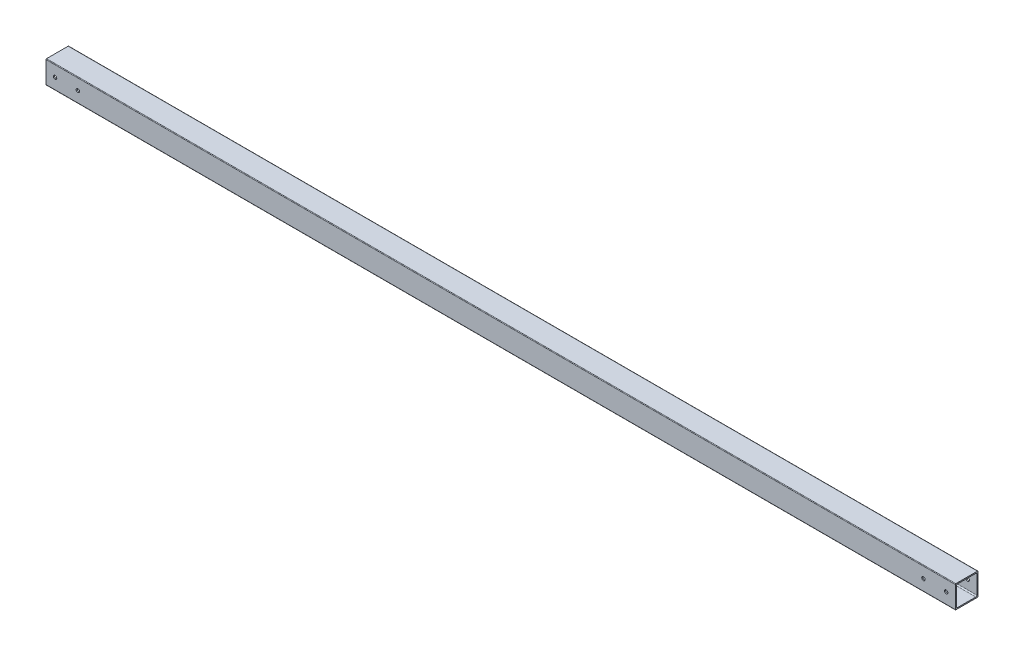
SolidWorks part; units mm, degrees
material "Thornel Mat VMA"
ref_plane "Front Plane" through (0, 0, 0) normal (0, 0, 1) x (1, 0, 0)
ref_plane "Top Plane" through (0, 0, 0) normal (0, 1, 0) x (1, 0, 0)
ref_plane "Right Plane" through (0, 0, 0) normal (1, 0, 0) x (0, 0, -1)
sketch "Sketch1" plane through (0, 0, 0) normal (1, 0, 0) x (0, 0, -1)
  line L1 (-9.5, -10) -> (9.5, -10)
  line L2 (-10, -9.5) -> (-10, 9.5)
  line L3 (-9.5, 10) -> (9.5, 10)
  line L4 (10, -9.5) -> (10, 9.5)
  line L5 (-10, -10) -> (10, 10) construction
  line L6 (-10, 10) -> (10, -10) construction
  line L7 (-8, -9) -> (8, -9)
  line L8 (-9, -8) -> (-9, 8)
  line L9 (-8, 9) -> (8, 9)
  line L10 (9, -8) -> (9, 8)
  line L11 (-9, -9) -> (9, 9) construction
  line L12 (-9, 9) -> (9, -9) construction
  arc A0 (-9.5, -10) -> (-10, -9.5) centre (-9.5, -9.5) cw
  arc A1 (9.5, -10) -> (10, -9.5) centre (9.5, -9.5) ccw
  arc A2 (9.5, 10) -> (10, 9.5) centre (9.5, 9.5) cw
  arc A3 (-10, 9.5) -> (-9.5, 10) centre (-9.5, 9.5) cw
  arc A4 (-8, -9) -> (-9, -8) centre (-8, -8) cw
  arc A5 (8, -9) -> (9, -8) centre (8, -8) ccw
  arc A6 (8, 9) -> (9, 8) centre (8, 8) cw
  arc A7 (-9, 8) -> (-8, 9) centre (-8, 8) cw
  point P0 (0, 0)
  point P6 (0, 0)
  dimension "D5" = 0.5
  dimension "D6" = 1
  dimension "D1" = 20
  dimension "D2" = 20
  dimension "D3" = 1
  dimension "D4" = 1
extrude "Boss-Extrude1" add sketch "Sketch1" along normal blind 800
sketch "Sketch2" plane through (0, 0, 10) normal (0, 0, 1) x (1, 0, 0)
  line L0 (800, 9.5) -> (800, -9.5) construction
  line L1 (800, 10) -> (0, 10) construction
  circle A0 centre (792, 0) radius 1.5
  circle A1 centre (772, 0) radius 1.5
  dimension "D1" = 3
  dimension "D2" = 3
  dimension "D3" = 20
  dimension "D4" = 8
extrude "Cut-Extrude1" cut sketch "Sketch2" against normal blind 205
sketch "Sketch3" plane through (0, 0, 10) normal (0, 0, 1) x (1, 0, 0)
  line L0 (0, 9.5) -> (0, -9.5) construction
  circle A0 centre (8, 0) radius 1.5
  circle A1 centre (28, 0) radius 1.5
  dimension "D1" = 3
  dimension "D2" = 3
  dimension "D3" = 20
  dimension "D4" = 8
extrude "Cut-Extrude2" cut sketch "Sketch3" against normal blind 25
